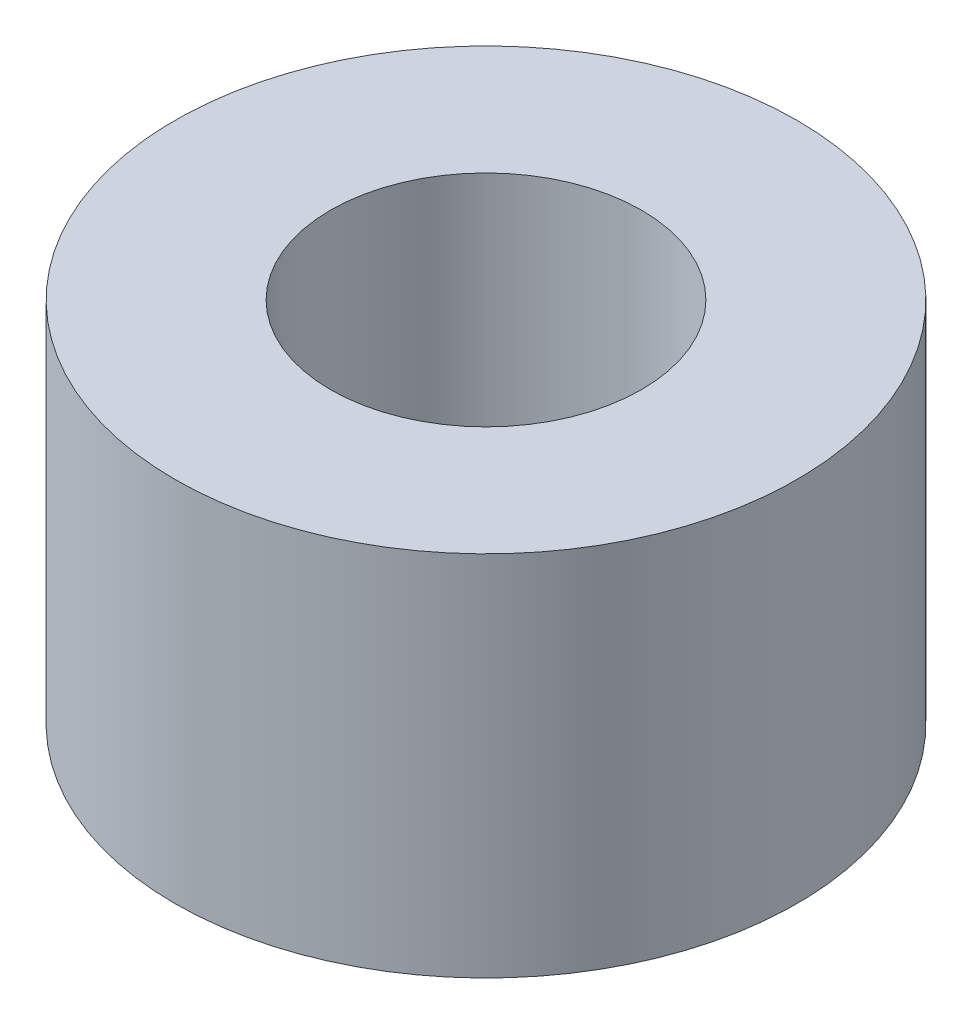
SolidWorks part; units mm, degrees
ref_plane "Front Plane" through (0, 0, 0) normal (0, 0, 1) x (1, 0, 0)
ref_plane "Top Plane" through (0, 0, 0) normal (0, 1, 0) x (1, 0, 0)
ref_plane "Right Plane" through (0, 0, 0) normal (1, 0, 0) x (0, 0, -1)
sketch "Sketch1" plane through (0, 0, 0) normal (0, 1, 0) x (1, 0, 0)
  circle A0 centre (0, 0) radius 6.35
  circle A1 centre (0, 0) radius 12.7
  dimension "D1" = 12.7
  dimension "D2" = 6.35
extrude "Boss-Extrude1" add sketch "Sketch1" along normal blind 15
